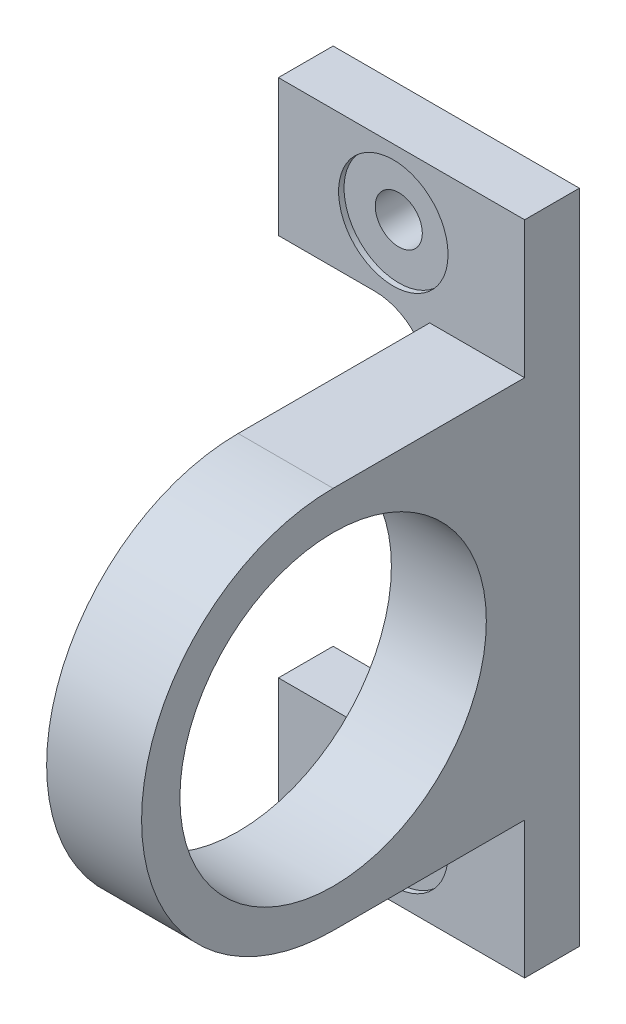
SolidWorks part; units mm, degrees
ref_plane "前视基准面" through (0, 0, 0) normal (0, 0, 1) x (1, 0, 0)
ref_plane "上视基准面" through (0, 0, 0) normal (0, 1, 0) x (1, 0, 0)
ref_plane "右视基准面" through (0, 0, 0) normal (1, 0, 0) x (0, 0, -1)
sketch "草图2" plane through (0, 0, 0) normal (0, 0, 1) x (1, 0, 0)
  line L0 (-14.7736, 24.3382) -> (-14.7736, -35.6618)
  line L1 (-14.7736, -35.6618) -> (30.2264, -35.6618)
  line L2 (7.7264, -35.6618) -> (7.7264, -23.1618)
  line L3 (21.55, -23.1618) -> (-6.0971, -23.1618)
  line L4 (-6.0971, -23.1618) -> (-6.0971, 11.8382)
  line L5 (-6.0971, 11.8382) -> (21.55, 11.8382)
  line L6 (7.7264, 11.8382) -> (7.7264, 24.3382)
  line L7 (30.2264, 24.3382) -> (-14.7736, 24.3382)
  line L8 (7.7264, 28.8603) -> (7.7264, -39.8897) construction
  line L9 (21.55, -23.1618) -> (21.55, 11.8382)
  line L10 (30.2264, 24.3382) -> (30.2264, -35.6618)
  line L11 (-18.1559, -5.6618) -> (33.2411, -5.6618) construction
  line L12 (44.0218, -5.6618) -> (44.0218, 26.2521) construction
  point P16 (-6.0971, -5.6618)
  point P17 (-14.7736, -5.6618)
  dimension "D1" = 45
  dimension "D2" = 35
  dimension "D3" = 60
extrude "凸台-拉伸2" add sketch "草图2" along normal blind 5 contours L6 L7 L0 L1 L2 L3 L4 L5 | L10 L7 L6 L5 L9 L3 L2 L1
sketch "草图4" plane through (0, 0, 5) normal (0, 0, 1) x (1, 0, 0)
  line L0 (-18.165, -5.6618) -> (33.9165, -5.6618) construction
  line L1 (-14.7736, 24.3382) -> (-14.7736, -35.6618) construction
  line L2 (-14.7736, -23.1618) -> (-6.0971, -23.1618)
  line L3 (-14.7736, -23.1618) -> (-14.7736, 11.8382)
  line L4 (-14.7736, 11.8382) -> (-6.0971, 11.8382)
  line L5 (-6.0971, -23.1618) -> (-6.0971, 11.8382)
  line L6 (-6.0971, -23.1618) -> (-6.0971, 11.8382) construction
  line L7 (7.7264, -39.813) -> (7.7264, 28.1228) construction
  line L8 (30.2264, 11.8382) -> (21.55, 11.8382)
  line L9 (21.55, -23.1618) -> (21.55, 11.8382)
  line L10 (30.2264, -23.1618) -> (21.55, -23.1618)
  line L11 (30.2264, -23.1618) -> (30.2264, 11.8382)
  point P17 (-14.7736, -5.6618)
  dimension "D1" = 35
extrude "凸台-拉伸15" add sketch "草图4" along normal blind 35
sketch "草图5" plane through (-14.7736, 0, 0) normal (-1, 0, 0) x (0, 0, 1)
  line L0 (0, -5.6618) -> (40, -5.6618)
  line L1 (0, 24.3382) -> (0, -35.6618) construction
  line L2 (40, 11.8382) -> (40, -23.1618) construction
  line L3 (22.5, 11.8382) -> (40, 11.8382)
  line L4 (40, 11.8382) -> (40, -23.1618)
  line L5 (40, -23.1618) -> (22.5, -23.1618)
  circle A0 centre (22.5, -5.6618) radius 17.5
  line M5 (5, -23.1618) -> (40, -23.1618)
  line M6 (40, -23.1618) -> (40, 11.8382)
  line M7 (40, 11.8382) -> (5, 11.8382)
  dimension "D1" = 35
extrude "切除-拉伸1" cut sketch "草图5" against normal blind 45 contours A0 M5 M6 | A0 M6 M7
sketch "草图6" plane through (-14.7736, 0, 0) normal (-1, 0, 0) x (0, 0, 1)
  circle A0 centre (22.5, -5.6618) radius 14
  dimension "D1" = 28
extrude "切除-拉伸2" cut sketch "草图6" against normal blind 45
fillet "圆角1" radius 5 4 edges at (-6.0971, 11.8382, 2.5) (21.55, 11.8382, 2.5) (-6.0971, -23.1618, 2.5) (21.55, -23.1618, 2.5)
sketch "草图7" plane through (-6.0971, 0, 0) normal (1, 0, 0) x (0, 0, -1)
  circle A0 centre (-22.5, -5.6618) radius 15
  circle A1 centre (-22.5, -5.6618) radius 13
extrude "凸台-拉伸16" add sketch "草图7" against normal blind 1
sketch "草图8" plane through (21.55, 0, 0) normal (-1, 0, 0) x (0, 0, 1)
  circle A0 centre (22.5, -5.6618) radius 15
  circle A1 centre (22.5, -5.6618) radius 10
sketch "草图9" plane through (0, 0, 5) normal (0, 0, 1) x (1, 0, 0)
  line L0 (7.7264, 24.3382) -> (7.7264, -35.6618)
  line L13 (30.2264, 24.3382) -> (-14.7736, 24.3382) construction
  line L14 (-14.7736, -35.6618) -> (30.2264, -35.6618) construction
sketch "草图11" plane through (0, 0, 5) normal (0, 0, 1) x (1, 0, 0)
  line L0 (-14.7736, 18.0882) -> (30.2264, 18.0882)
  line L1 (-14.7736, 24.3382) -> (-14.7736, 11.8382) construction
  line L2 (30.2264, 24.3382) -> (30.2264, 11.8382) construction
  line L3 (7.7264, 24.3382) -> (7.7264, -35.6618) construction
  line L4 (30.2264, 24.3382) -> (-14.7736, 24.3382) construction
  line L5 (-14.7736, -35.6618) -> (30.2264, -35.6618) construction
  line L6 (7.7264, -5.6618) -> (45.6912, -5.6618) construction
  line L10 (-14.7736, -29.4118) -> (30.2264, -29.4118)
  line L11 (-14.7736, -23.1618) -> (-14.7736, -35.6618) construction
  point P4 (-2.7736, 18.0882)
  point P16 (-2.7736, -29.4118)
  point P18 (18.2264, -29.4118)
  point P25 (18.2264, 18.0882)
  dimension "D1" = 12
split "分割1" trim tools "草图9" bodies to split 111 resulting bodies 117 118
delete or keep bodies "实体-删除/保留 2" type delete bodies bodies 117
hole_wizard "打孔尺寸(%根据六角头螺)栓 全螺纹的类型1" positions "3D草图2" profile "草图13" counterbore size "M4" standard "GB"
sketch3d "3D草图2"
  point P0 (18.2264, 18.0882, 5)
  point P3 (18.2264, -29.4118, 5)
sketch "草图13" plane through (18.2264, 18.0882, 5) normal (1, 0, 0) x (0, -1, 0)
  line L0 (0, 0) -> (0, 6.2919)
  line L1 (0, 6.2919) -> (2.15, 5)
  line L2 (2.15, 5) -> (2.15, 0.5)
  line L3 (2.15, 0.5) -> (5, 0.5)
  line L4 (5, 0.5) -> (5, 0)
  line L5 (5, 0) -> (0, 0)
  line L10 (0, 6.2919) -> (-2.15, 5) construction
  line L11 (0, -6.35) -> (0, 107.95) construction
  dimension "孔直径" = 4.3
  dimension "孔深度" = 5
  dimension "柱形沉头孔直径" = 10
  dimension "柱形沉头孔深度" = 0.5
  dimension "导头角度" = 118
